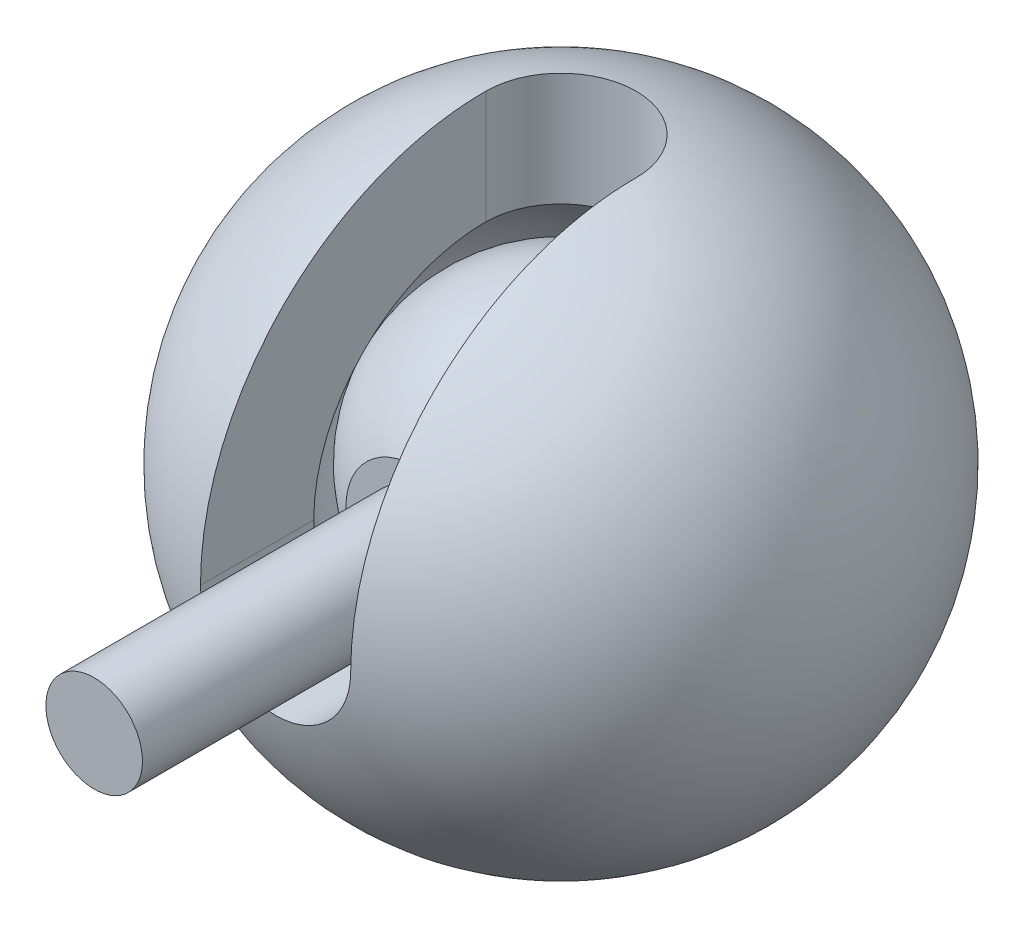
SolidWorks part; units mm, degrees
ref_plane "Front Plane" through (0, 0, 0) normal (0, 0, 1) x (1, 0, 0)
ref_plane "Top Plane" through (0, 0, 0) normal (0, 1, 0) x (1, 0, 0)
ref_plane "Right Plane" through (0, 0, 0) normal (1, 0, 0) x (0, 0, -1)
sketch "Sketch1" plane through (0, 0, 0) normal (0, 0, 1) x (1, 0, 0)
  line L0 (0, -7.5) -> (0, 7.5) construction
  line L1 (0, 7.5) -> (0, -7.5)
  arc A0 (0, -7.5) -> (0, 7.5) centre (0, 0) cw
  point P4 (0, 0)
  dimension "D1" = 15
revolve "Revolve1" add sketch "Sketch1" angle 360 about L0
sketch "Sketch2" plane through (0, 0, 0) normal (0, 0, 1) x (1, 0, 0)
  line L1 (0, 7.5) -> (0, -7.5) construction
  arc A0 (0, 8.75) -> (0, -8.75) centre (0, 0) ccw
  dimension "D1" = 8.75
revolve "Revolve-Thin2" add sketch "Sketch2" angle 360 about L1
ref_plane "Plane1" through (0, 0, 13.75) normal (0, 0, 1) x (1, 0, 0)
sketch "Sketch4" plane through (0, 0, 13.75) normal (0, 0, 1) x (1, 0, 0)
  circle A0 centre (0, 0) radius 3.5
  dimension "D1" = 7
extrude "Cut-Extrude3" cut sketch "Sketch4" against normal blind 7
sketch "Sketch11" plane through (0, 0, 0) normal (1, 0, 0) x (0, 0, -1)
  arc A0 (0, 13.75) -> (-13.75, 0) centre (0, 0) ccw
  arc A1 (-13.2971, -3.5) -> (-13.2971, 3.5) centre (0, 0) ccw construction
sketch "Sketch12" plane through (0, 0, 0) normal (0, 1, 0) x (1, 0, 0)
  line L0 (-15.125, -13.75) -> (15.125, -13.75) construction
  line L1 (-3.5, -19.705) -> (3.5, -19.705)
  line L2 (-3.5, -19.705) -> (-3.5, -7.795)
  line L3 (-3.5, -7.795) -> (3.5, -7.795)
  line L4 (3.5, -19.705) -> (3.5, -7.795)
  line L5 (-3.5, -19.705) -> (3.5, -7.795) construction
  line L6 (-3.5, -7.795) -> (3.5, -19.705) construction
  line L7 (0, -13.75) -> (0, 0) construction
  point P0 (0, -13.75)
  dimension "D1" = 7
sweep "Cut-Sweep2" cut profiles "Sketch12" path "Sketch11"
ref_plane "Plane2" through (0, 13.75, 0) normal (0, 1, 0) x (1, 0, 0)
sketch "Sketch13" plane through (0, 13.75, 0) normal (0, 1, 0) x (1, 0, 0)
  circle A0 centre (0, 0) radius 3.5
extrude "Cut-Extrude4" cut sketch "Sketch13" against normal blind 6
sketch "Sketch14" plane through (0, 0, 6.75) normal (0, 0, 1) x (1, 0, 0)
  circle A1 centre (0, 0) radius 3.2692 construction
  circle A2 centre (0, 0) radius 2.25
  dimension "D1" = 4.5
extrude "Boss-Extrude3" add sketch "Sketch14" along normal blind 15
